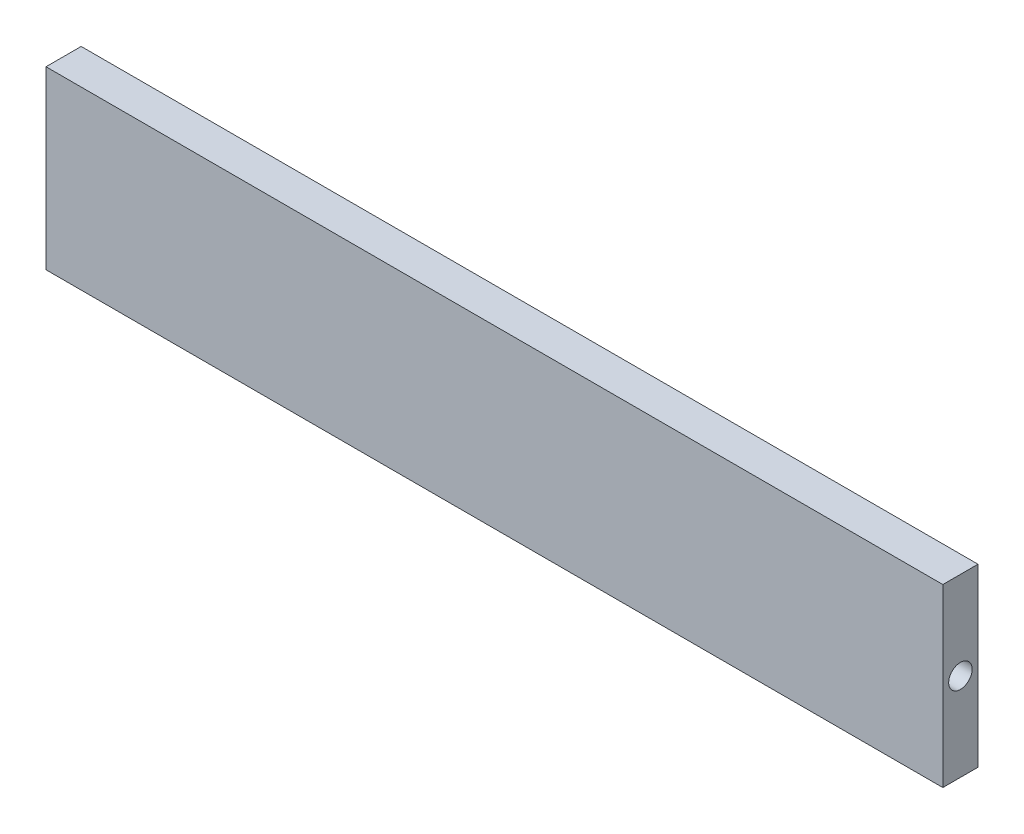
SolidWorks part; units mm, degrees
ref_plane "Front Plane" through (0, 0, 0) normal (0, 0, 1) x (1, 0, 0)
ref_plane "Top Plane" through (0, 0, 0) normal (0, 1, 0) x (1, 0, 0)
ref_plane "Right Plane" through (0, 0, 0) normal (1, 0, 0) x (0, 0, -1)
sketch "Sketch1" plane through (0, 0, 0) normal (0, 0, 1) x (1, 0, 0)
  line L1 (38.25, 7.5) -> (-38.25, 7.5)
  line L2 (38.25, 7.5) -> (38.25, -7.5)
  line L3 (38.25, -7.5) -> (-38.25, -7.5)
  line L4 (-38.25, 7.5) -> (-38.25, -7.5)
  line L5 (38.25, 7.5) -> (-38.25, -7.5) construction
  line L6 (38.25, -7.5) -> (-38.25, 7.5) construction
  point P0 (0, 0)
  dimension "D1" = 76.5
  dimension "D2" = 15
extrude "Boss-Extrude1" add sketch "Sketch1" along normal blind 3
sketch "Sketch2" plane through (38.25, 0, 0) normal (1, 0, 0) x (0, 0, -1)
  line L0 (-1.5, 7.5) -> (-1.5, -7.5) construction
  line L1 (-3, 7.5) -> (0, 7.5) construction
  line L2 (-3, -7.5) -> (0, -7.5) construction
  line L3 (-1.5, -7.5) -> (0, 0) construction
  line L4 (0, -7.5) -> (0, 7.5) construction
  line L5 (0, 0) -> (-1.5, 0) construction
  circle A0 centre (-1.5, 0) radius 1
  dimension "D1" = 2
extrude "Cut-Extrude1" cut sketch "Sketch2" against normal through all
